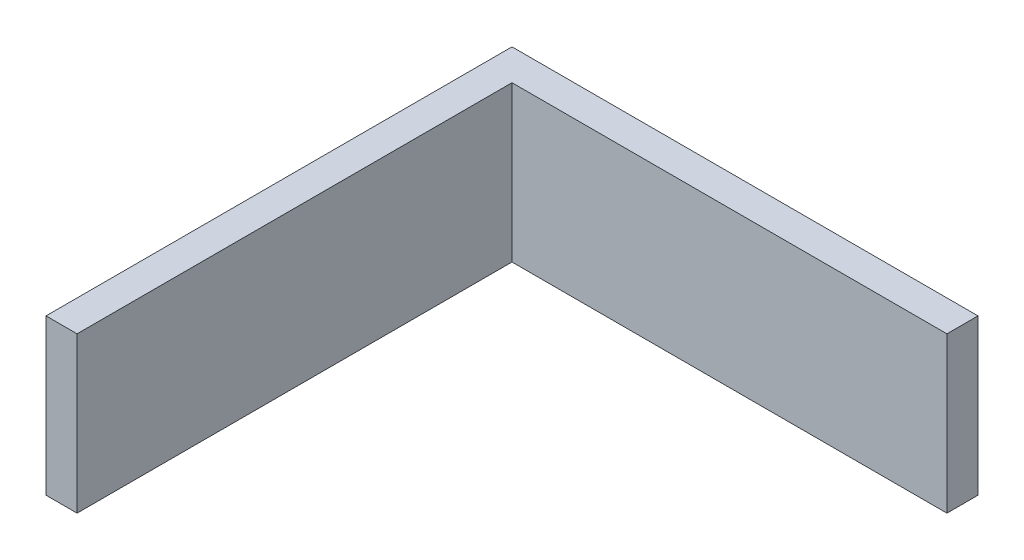
SolidWorks part; units mm, degrees
ref_plane "Front Plane" through (0, 0, 0) normal (0, 0, 1) x (1, 0, 0)
ref_plane "Top Plane" through (0, 0, 0) normal (0, 1, 0) x (1, 0, 0)
ref_plane "Right Plane" through (0, 0, 0) normal (1, 0, 0) x (0, 0, -1)
sketch "Sketch1" plane through (0, 0, 0) normal (0, 1, 0) x (1, 0, 0)
  line L1 (0, 0) -> (-2, 0)
  line L2 (0, 0) -> (0, -30)
  line L3 (0, -30) -> (-2, -30)
  line L4 (-2, 0) -> (-2, -30)
  line L5 (0, 0) -> (28, 0)
  line L6 (0, 0) -> (0, -2)
  line L7 (0, -2) -> (28, -2)
  line L8 (28, 0) -> (28, -2)
  dimension "D1" = 30
  dimension "D2" = 28
  dimension "D3" = 2
  dimension "D4" = 2
extrude "Boss-Extrude1" add sketch "Sketch1" along normal blind 10 contours L1 L4 L3 L2 | L8 L5 L2 L7
